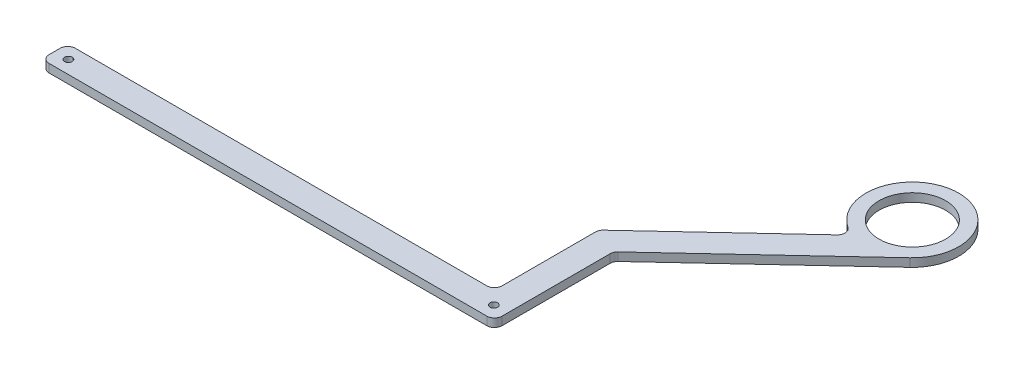
SolidWorks part; units mm, degrees
ref_plane "Front Plane" through (0, 0, 0) normal (0, 0, 1) x (1, 0, 0)
ref_plane "Top Plane" through (0, 0, 0) normal (0, 1, 0) x (1, 0, 0)
ref_plane "Right Plane" through (0, 0, 0) normal (1, 0, 0) x (0, 0, -1)
sketch "Sketch1" plane through (0, 0, 0) normal (0, 1, 0) x (1, 0, 0)
  line L0 (0, 0) -> (172.7, 0)
  line L1 (172.7, 0) -> (172.7, 45.39)
  line L2 (172.7, 45.39) -> (231.2083, 99.9499)
  line L4 (212.7325, 96.3941) -> (162.7, 49.7381)
  line L5 (162.7, 49.7381) -> (162.7, 10)
  line L6 (162.7, 10) -> (0, 10)
  line L7 (0, 10) -> (0, 0)
  line L8 (0, 5) -> (5.25, 5) construction
  line L9 (167.45, 5) -> (172.7, 5) construction
  circle A0 centre (5.25, 5) radius 1.4605
  circle A1 centre (167.45, 5) radius 1.4605
  circle A2 centre (219.1369, 112.8948) radius 12.7
  arc A3 (231.2083, 99.9499) -> (212.7325, 96.3941) centre (219.1369, 112.8948) ccw
  point P17 (213.7505, 97.0836)
  point P18 (0, 0)
  point P20 (0, 0)
  dimension "D5" = 2.921
  dimension "D6" = 5
  dimension "D7" = 162.2
  dimension "D11" = 25.4
  dimension "D1" = 10
  dimension "D2" = 10
  dimension "D3" = 10
  dimension "D4" = 133
  dimension "D8" = 172.7
  dimension "D9" = 45.39
  dimension "D10" = 80
  dimension "D12" = 5
extrude "Boss-Extrude1" add sketch "Sketch1" along normal blind 3.175
fillet "Fillet1" radius 2.921 7 edges at (162.7, 1.5875, -49.7381) (162.7, 1.5875, -10) (0, 1.5875, 0) (0, 1.5875, -10) (172.7, 1.5875, -45.39) (172.7, 1.5875, 0) (212.7325, 1.5875, -96.3941)
